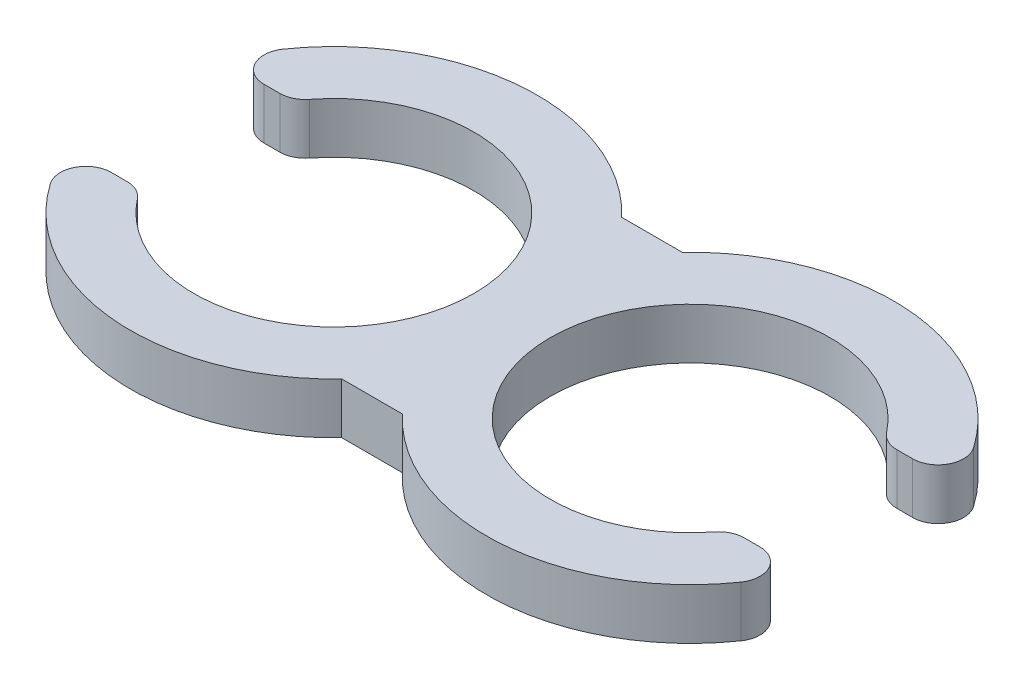
SolidWorks part; units mm, degrees
ref_plane "Front Plane" through (0, 0, 0) normal (0, 0, 1) x (1, 0, 0)
ref_plane "Top Plane" through (0, 0, 0) normal (0, 1, 0) x (1, 0, 0)
ref_plane "Right Plane" through (0, 0, 0) normal (1, 0, 0) x (0, 0, -1)
sketch "Sketch1" plane through (0, 0, 0) normal (0, 1, 0) x (1, 0, 0)
  line L1 (-7, -5.5) -> (7, -5.5)
  line L2 (-7, -5.5) -> (-7, 5.5)
  line L3 (-7, 5.5) -> (7, 5.5)
  line L4 (7, -5.5) -> (7, 5.5)
  line L5 (-3.127, 7) -> (3.127, 7)
  line L6 (-3.127, 7) -> (-3.127, -7)
  line L7 (-3.127, -7) -> (3.127, -7)
  line L8 (3.127, 7) -> (3.127, -7)
  line L9 (14.4162, 3) -> (-14.4162, 3)
  line L10 (14.4162, 3) -> (14.4162, -3)
  line L11 (14.4162, -3) -> (-14.4162, -3)
  line L12 (-14.4162, 3) -> (-14.4162, -3)
  circle A0 centre (7, 0) radius 5.5
  circle A1 centre (-7, 0) radius 5.5
  circle A2 centre (7, 0) radius 8
  circle A3 centre (-7, 0) radius 8
  point P15 (0, 0)
  point P20 (14.7667, -1.918)
  dimension "D5" = 16
  dimension "D1" = 14
  dimension "D2" = 11
  dimension "D3" = 5.5
  dimension "D4" = 7
  dimension "D6" = 14
  dimension "D7" = 6
extrude "Boss-Extrude1" add sketch "Sketch1" along normal blind 2 contours L9 A2 L8 L3 A0 | L8 A2 L11 A0 L1 | L1 A2 L8 | A3 A2 L1 L8 A0 L11 | A3 L11 A0 L9 | A3 L9 A0 L8 L3 A2 | A3 A2 L3 | A2 A3 L3 L6 A1 L9 | A2 L9 A1 L11 | L1 A3 A2 L11 A1 L6 | A3 L1 A2 | L11 A3 L9 A2 | L9 A3 A2 | A2 A3 L11 | A1 L6 L3 | L6 A3 L9 A1 L3 | L3 A3 L6 | L8 A2 L3 | L6 A3 L1 | L11 A3 L6 L1 A1 | A1 L1 L6 | A0 L3 L8 | A0 L8 L1
fillet "Fillet1" radius 1 4 edges at (14.4162, 1, -3) (14.4162, 1, 3) (-14.4162, 1, 3) (-14.4162, 1, -3)
fillet "Fillet2" radius 1 4 edges at (11.6098, 1, 3) (11.6098, 1, -3) (-11.6098, 1, 3) (-11.6098, 1, -3)
